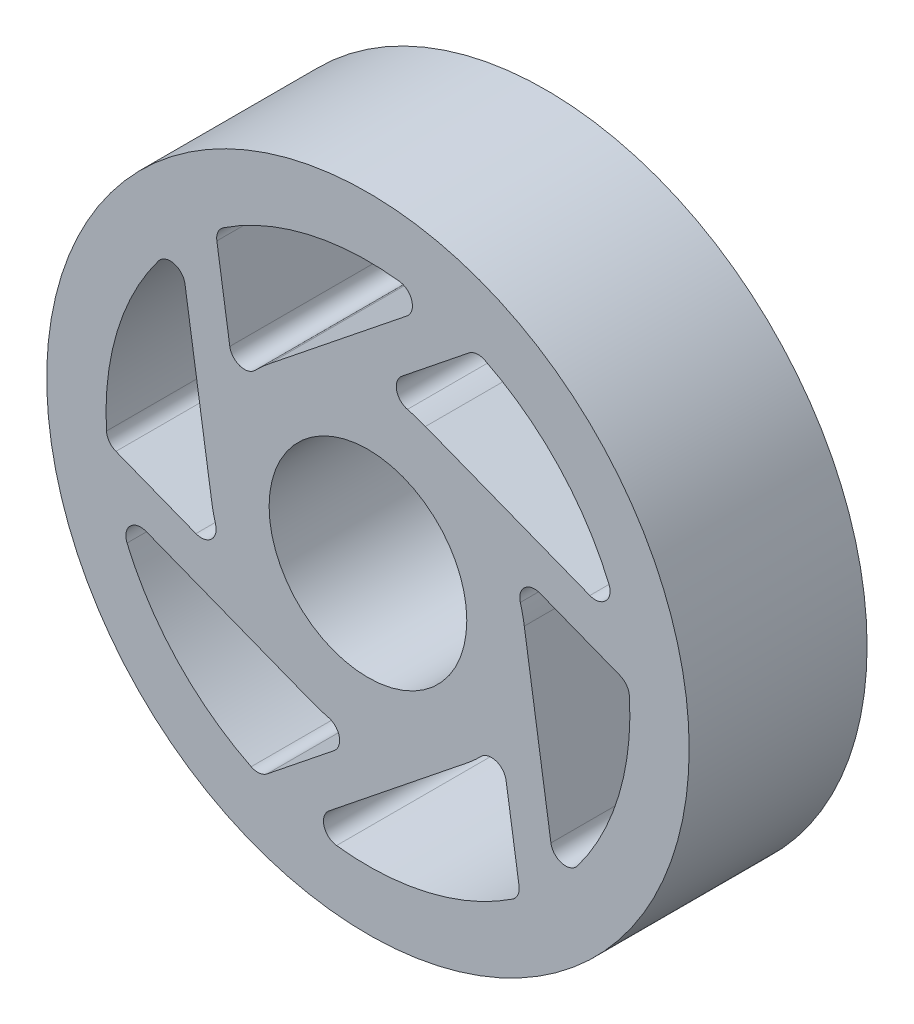
SolidWorks part; units mm, degrees
material "ABS"
ref_plane "前视基准面" through (0, 0, 0) normal (0, 0, 1) x (1, 0, 0)
ref_plane "上视基准面" through (0, 0, 0) normal (0, 1, 0) x (1, 0, 0)
ref_plane "右视基准面" through (0, 0, 0) normal (1, 0, 0) x (0, 0, -1)
sketch "草图1" plane through (0, 0, 0) normal (0, 0, 1) x (1, 0, 0)
  circle A0 centre (0, 0) radius 32.5
  circle A1 centre (0, 0) radius 5
  dimension "D1" = 65
  dimension "D2" = 10
extrude "凸台-拉伸1" add sketch "草图1" along normal mid plane 18
sketch "草图2" plane through (0, 0, 9) normal (0, 0, 1) x (1, 0, 0)
  circle A0 centre (0, 0) radius 10
  dimension "D1" = 20
extrude "切除-拉伸2" cut sketch "草图2" against normal blind 15
sketch "草图3" plane through (0, 0, 9) normal (0, 0, 1) x (1, 0, 0)
  line L0 (0, 0) -> (0, 26.5) construction
  line L1 (-10, 12.49) -> (6.4904, 25.6929)
  line L2 (-10, 12.49) -> (0, 12.49) construction
  line L3 (5.8167, 14.9053) -> (25.4959, 7.2256)
  line L4 (15.8167, 2.4153) -> (19.0055, -18.4673)
  line L5 (10, -12.49) -> (-6.4904, -25.6929)
  line L6 (-5.8167, -14.9053) -> (-25.4959, -7.2256)
  line L7 (-15.8167, -2.4153) -> (-19.0055, 18.4673)
  line L8 (-15.7614, 2.7531) -> (10.9441, 24.1346)
  line L9 (-7.5, 9.3675) -> (8.9904, 22.5704) construction
  line L10 (-5.4964, 15.0263) -> (26.3732, 2.5894)
  line L11 (10.2649, 12.2732) -> (15.4291, -21.5451)
  line L12 (15.7614, -2.7531) -> (-10.9441, -24.1346)
  line L13 (5.4964, -15.0263) -> (-26.3732, -2.5894)
  line L14 (-10.2649, -12.2732) -> (-15.4291, 21.5451)
  circle A0 centre (0, 0) radius 16
  circle A1 centre (0, 0) radius 10 construction
  circle A2 centre (0, 0) radius 26.5
  circle A3 centre (0, 0) radius 32.5 construction
  point P24 (0, 0)
  point P31 (0, 0)
  point P39 (0, 0)
  dimension "D1" = 6
  dimension "D2" = 6
  dimension "D3" = 10
  dimension "D5" = 4
  dimension "D4" = 6
  dimension "D6" = 6
extrude "切除-拉伸3" cut sketch "草图3" against normal blind 45 contours L1 A2 L14 A0 | L3 A2 L8 A0 | L4 A2 L10 A0 | L5 A2 L11 A0 | L6 A2 L12 A0 | L7 A2 L13 A0
fillet "圆角1" radius 1.5 18 edges at (-13.46, 8.6503, 0) (-15.4291, 21.5451, 0) (6.4904, 25.6929, 0) (-14.2214, -7.3316, 0) (-26.3732, -2.5894, 0) (-19.0055, 18.4673, 0) (14.2214, 7.3316, 0) (26.3732, 2.5894, 0) (0.7614, 15.9819, 0) (10.9441, 24.1346, 0) (25.4959, 7.2256, 0) (-0.7614, -15.9819, 0) (-25.4959, -7.2256, 0) (19.0055, -18.4673, 0) (13.46, -8.6503, 0) (15.4291, -21.5451, 0) (-6.4904, -25.6929, 0) (-10.9441, -24.1346, 0)
